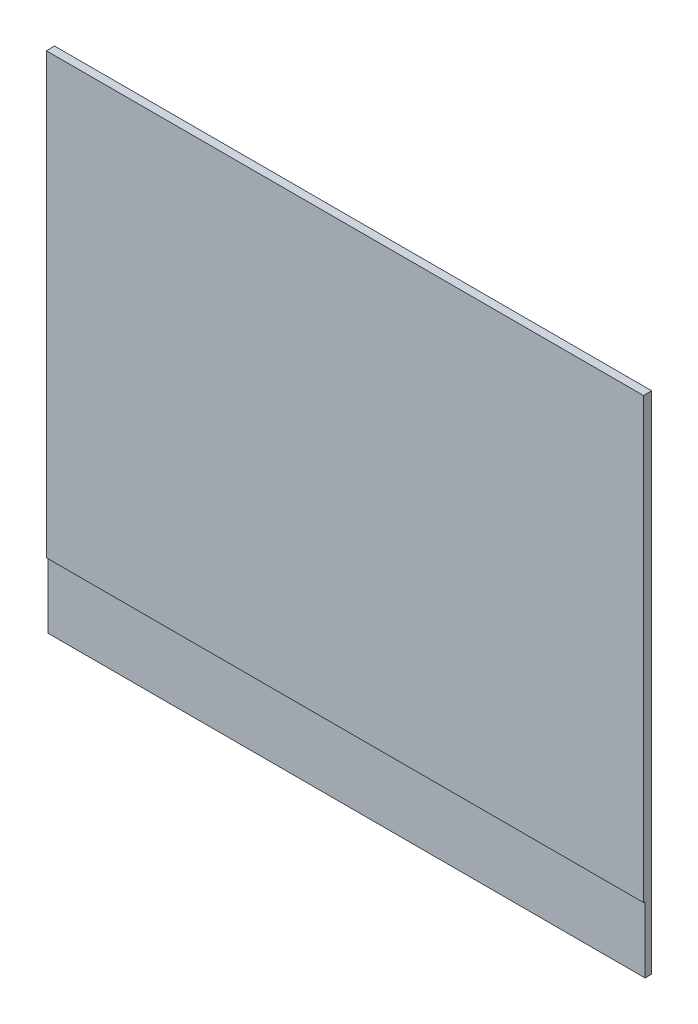
SolidWorks part; units mm, degrees
ref_plane "Plan de face" through (0, 0, 0) normal (0, 0, 1) x (1, 0, 0)
ref_plane "Plan de dessus" through (0, 0, 0) normal (0, 1, 0) x (1, 0, 0)
ref_plane "Plan de droite" through (0, 0, 0) normal (1, 0, 0) x (0, 0, -1)
sketch "Esquisse1" plane through (0, 0, 0) normal (0, 0, 1) x (1, 0, 0)
  line L1 (0, 0) -> (91, 0)
  line L2 (0, 0) -> (0, 77)
  line L3 (0, 77) -> (91, 77)
  line L4 (91, 0) -> (91, 77)
  dimension "D1" = 91
  dimension "D2" = 77
extrude "Boss.-Extru.1" add sketch "Esquisse1" along normal blind 1.25
sketch "Esquisse2" plane through (0, 0, 1.25) normal (0, 0, 1) x (1, 0, 0)
  line L0 (91, 0) -> (91, 77) construction
  line L1 (0, 0) -> (91, 0)
  line L2 (0, 0) -> (0, 10.0887)
  line L3 (0, 10.0887) -> (91, 10.0887)
  line L4 (91, 0) -> (91, 10.0887)
extrude "Enlèv. mat.-Extru.1" cut sketch "Esquisse2" against normal blind 0.25
